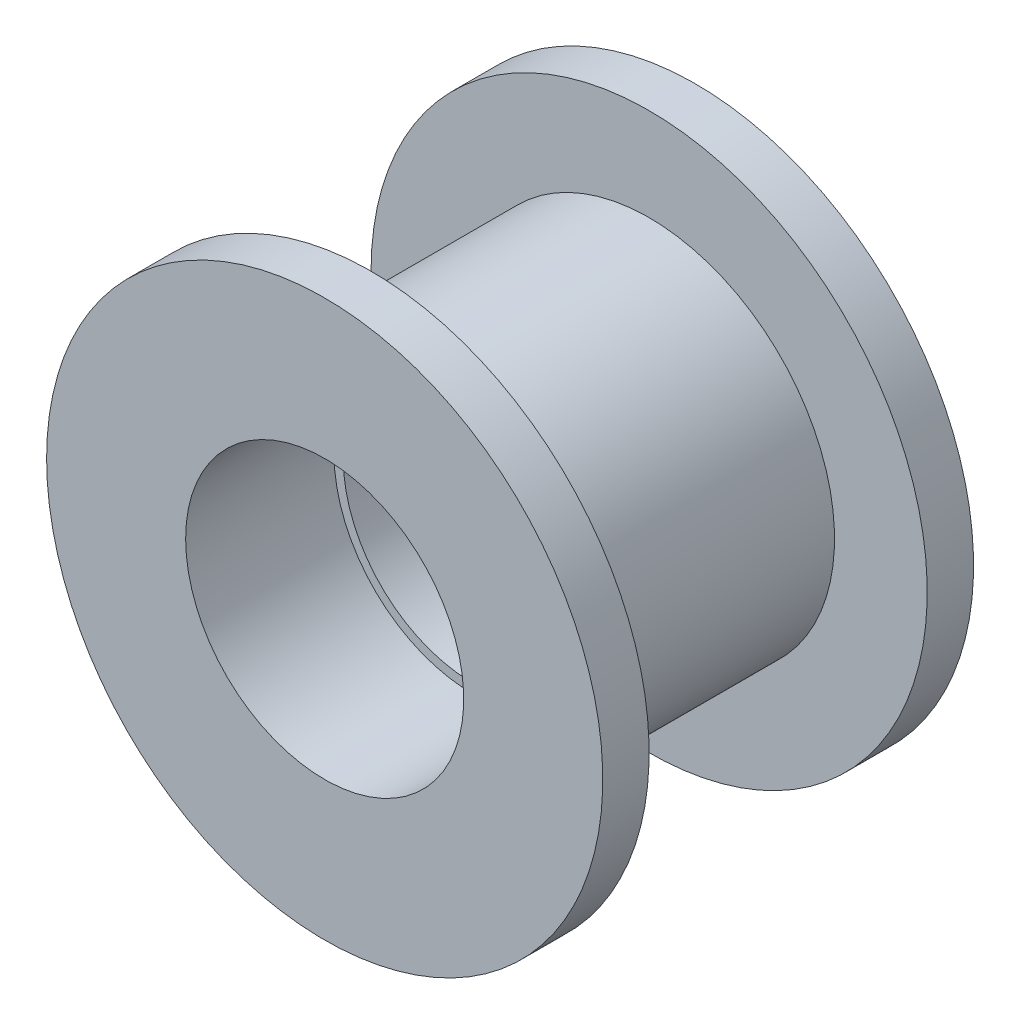
SolidWorks part; units mm, degrees
ref_plane "Front Plane" through (0, 0, 0) normal (0, 0, 1) x (1, 0, 0)
ref_plane "Top Plane" through (0, 0, 0) normal (0, 1, 0) x (1, 0, 0)
ref_plane "Right Plane" through (0, 0, 0) normal (1, 0, 0) x (0, 0, -1)
sketch "Sketch1" plane through (0, 0, 0) normal (0, 1, 0) x (1, 0, 0)
  line L0 (0, 89.8571) -> (0, -51.2857) construction
  line L1 (-87.4286, 0) -> (14, 0) construction
  line L2 (15, 0) -> (30, 0)
  line L3 (30, 0) -> (30, 5)
  line L4 (30, 5) -> (20, 5)
  line L5 (20, 5) -> (20, 35)
  line L6 (20, 35) -> (30, 35)
  line L7 (30, 35) -> (30, 40)
  line L8 (30, 40) -> (14, 40)
  line L9 (14, 40) -> (14, 16)
  line L10 (14, 16) -> (15, 16)
  line L11 (15, 16) -> (15, 0)
  line L12 (15, 0) -> (84.2857, 0) construction
  dimension "D1" = 14
  dimension "D2" = 20
  dimension "D3" = 30
  dimension "D4" = 30
  dimension "D5" = 40
  dimension "D6" = 5
  dimension "D7" = 5
  dimension "D8" = 15
  dimension "D9" = 16
revolve "Revolve1" add sketch "Sketch1" angle 360 about L0
sketch "Sketch2" plane through (0, 0, -40) normal (0, 0, -1) x (-1, 0, 0)
  line L0 (-52.4574, 0) -> (49.9227, 0) construction
  line L1 (0, -28.3777) -> (0, 34.4389) construction
  line L2 (-5.5826, 14) -> (5.0006, 14) construction
  line L3 (-4, 17.3) -> (4, 17.3) construction
  line L4 (-4, 17.3) -> (-4, 9.3) construction
  line L5 (-4, 9.3) -> (4, 9.3) construction
  line L6 (4, 17.3) -> (4, 9.3) construction
  line L7 (-4, 17.3) -> (4, 17.3)
  line L8 (4, 17.3) -> (4, 13.4164)
  line L9 (-4, 17.3) -> (-4, 13.4164)
  circle A0 centre (0, 0) radius 14
  point P11 (0, 14)
  circle M9 centre (0, 0) radius 14
  dimension "D4" = 28
  dimension "D1" = 8
  dimension "D2" = 4
  dimension "D3" = 8
  dimension "D5" = 3.3
extrude "Cut-Extrude1" cut sketch "Sketch2" against normal blind 16 contours L7 L9 L8 M9
equation "\"spoolA_idA\"= 30"
equation "\"spoolA_idB\"=28"
equation "\"D1@Sketch1\"=\"spoolA_idB\"/2"
equation "\"spoolA_odA\" = 40"
equation "\"D2@Sketch1\"=\"spoolA_odA\"/2"
equation "\"spoolA_flangeA_odA\"=70"
equation "\"spoolA_flangeA_od\" = 60"
equation "\"D3@Sketch1\"=\"spoolA_flangeA_od\"/2"
equation "\"spoolA_flangeB_od\"= 60"
equation "\"D4@Sketch1\"=\"spoolA_flangeB_od\"/2"
equation "\"spoolA_length\"= 40"
equation "\"D5@Sketch1\"=\"spoolA_length\""
equation "\"spoolA_flangeA_lengthA\"=5"
equation "\"D6@Sketch1\"=\"spoolA_flangeA_lengthA\""
equation "\"spoolA_flangeB_length\"=5"
equation "\"D7@Sketch1\"=\"spoolA_flangeB_length\""
equation "\"spoolA_keywayC_b2\"=8"
equation "\"D1@Sketch2\"=\"spoolA_keywayC_b2\""
equation "\"D2@Sketch2\"=\"spoolA_keywayC_b2\"/2"
equation "\"spoolA_keywayD_h\"=8"
equation "\"D3@Sketch2\"=\"spoolA_keywayD_h\""
equation "\"D4@Sketch2\"=\"spoolA_idB\""
equation "\"spoolA_keywayD_t2\"=3.3"
equation "\"D5@Sketch2\"=\"spoolA_keywayD_t2\""
equation "\"spoolA_keywayD_l\"=16"
equation "\"D1@Cut-Extrude1\"=\"spoolA_keywayD_l\""
equation "\"D8@Sketch1\"=\"spoolA_idA\"/2"
equation "\"spoolA_lengthA\"=16"
equation "\"D9@Sketch1\"=\"spoolA_lengthA\""
